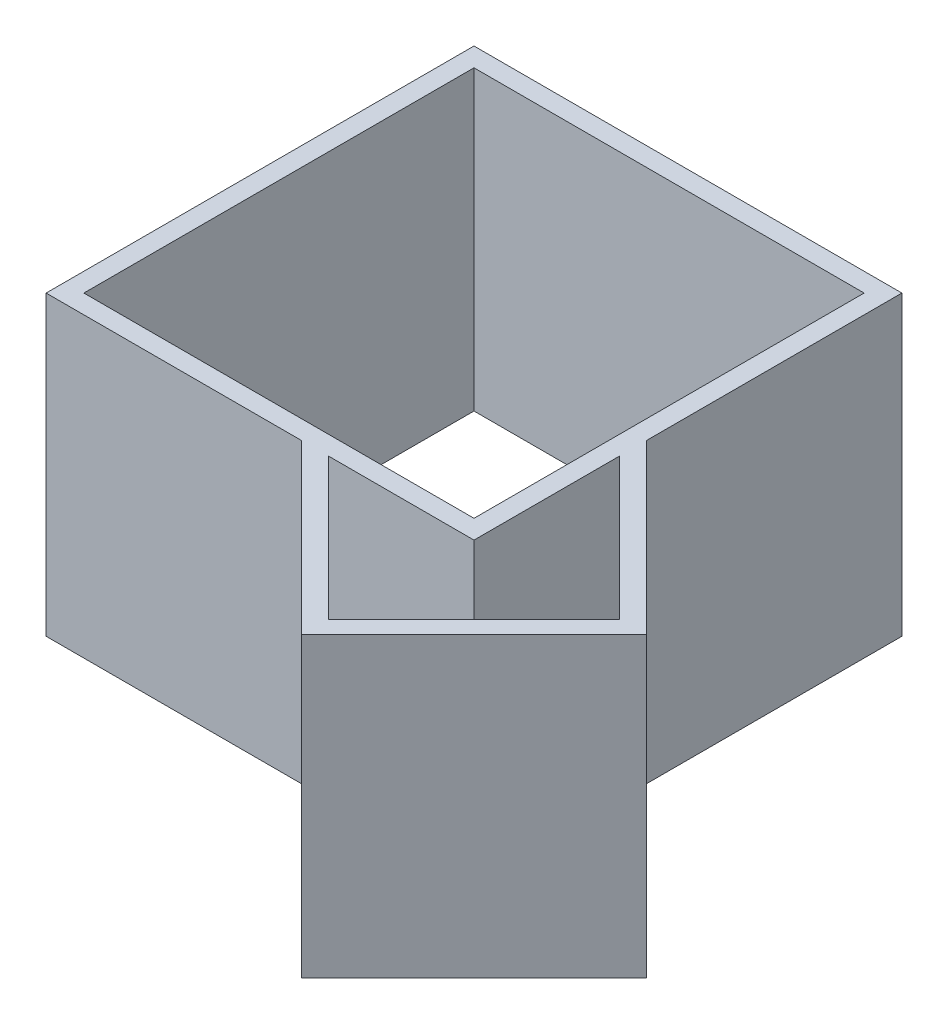
SolidWorks part; units mm, degrees
ref_plane "Front Plane" through (0, 0, 0) normal (0, 0, 1) x (1, 0, 0)
ref_plane "Top Plane" through (0, 0, 0) normal (0, 1, 0) x (1, 0, 0)
ref_plane "Right Plane" through (0, 0, 0) normal (1, 0, 0) x (0, 0, -1)
sketch "Sketch1" plane through (0, 0, 0) normal (0, 1, 0) x (1, 0, 0)
  line L1 (-35.985, -35.985) -> (35.985, -35.985)
  line L2 (-35.985, -35.985) -> (-35.985, 35.985)
  line L3 (-35.985, 35.985) -> (35.985, 35.985)
  line L4 (35.985, -35.985) -> (35.985, 35.985)
  line L5 (-35.985, -35.985) -> (35.985, 35.985) construction
  line L6 (-35.985, 35.985) -> (35.985, -35.985) construction
  line L7 (-32.81, -32.81) -> (32.81, -32.81)
  line L8 (-32.81, -32.81) -> (-32.81, 32.81)
  line L9 (-32.81, 32.81) -> (32.81, 32.81)
  line L10 (32.81, -32.81) -> (32.81, 32.81)
  line L11 (-32.81, -32.81) -> (32.81, 32.81) construction
  line L12 (-32.81, 32.81) -> (32.81, -32.81) construction
  point P0 (0, 0)
  point P6 (0, 0)
  point P11 (31.4493, 31.4493)
  dimension "D1" = 71.97
  dimension "D2" = 71.97
  dimension "D3" = 3.175
extrude "Boss-Extrude1" add sketch "Sketch1" along normal mid plane 50
sketch "Sketch2" plane through (0, 0, 0) normal (0, 1, 0) x (1, 0, 0)
  line L0 (0, 0) -> (35355.3391, -35355.3391) construction
  line L1 (35.2779, -64.2693) -> (6.9936, -35.985)
  line L2 (35.2779, -64.2693) -> (64.2693, -35.2779)
  line L3 (6.9936, -35.985) -> (11.4838, -35.985)
  line L4 (64.2693, -35.2779) -> (35.985, -6.9936)
  line L5 (35.2779, -64.2693) -> (35.985, -6.9936) construction
  line L6 (6.9936, -35.985) -> (64.2693, -35.2779) construction
  line L7 (35.985, -35.985) -> (35.985, 35.985) construction
  line L8 (11.4838, -35.985) -> (35.2779, -59.7791)
  line L9 (35.985, -11.4838) -> (35.985, -6.9936)
  line L10 (35.2779, -59.7791) -> (59.7791, -35.2779)
  line L11 (35.985, -11.4838) -> (59.7791, -35.2779)
  line L12 (11.4838, -35.985) -> (59.7791, -35.2779) construction
  line L13 (35.2779, -59.7791) -> (35.985, -11.4838) construction
  line L14 (-35.985, -35.985) -> (35.985, -35.985) construction
  point P5 (35.6314, -35.6314)
  point P13 (35.6314, -35.6314)
  dimension "D1" = 41
  dimension "D2" = 40
  dimension "D3" = 3.175
  dimension "D4" = 3.175
  dimension "D5" = 3.175
extrude "Boss-Extrude2" add sketch "Sketch2" along normal mid plane 50
equation "\"D4@Sketch2\"=\"D3@Sketch2\""
equation "\"D5@Sketch2\"=\"D3@Sketch2\""
